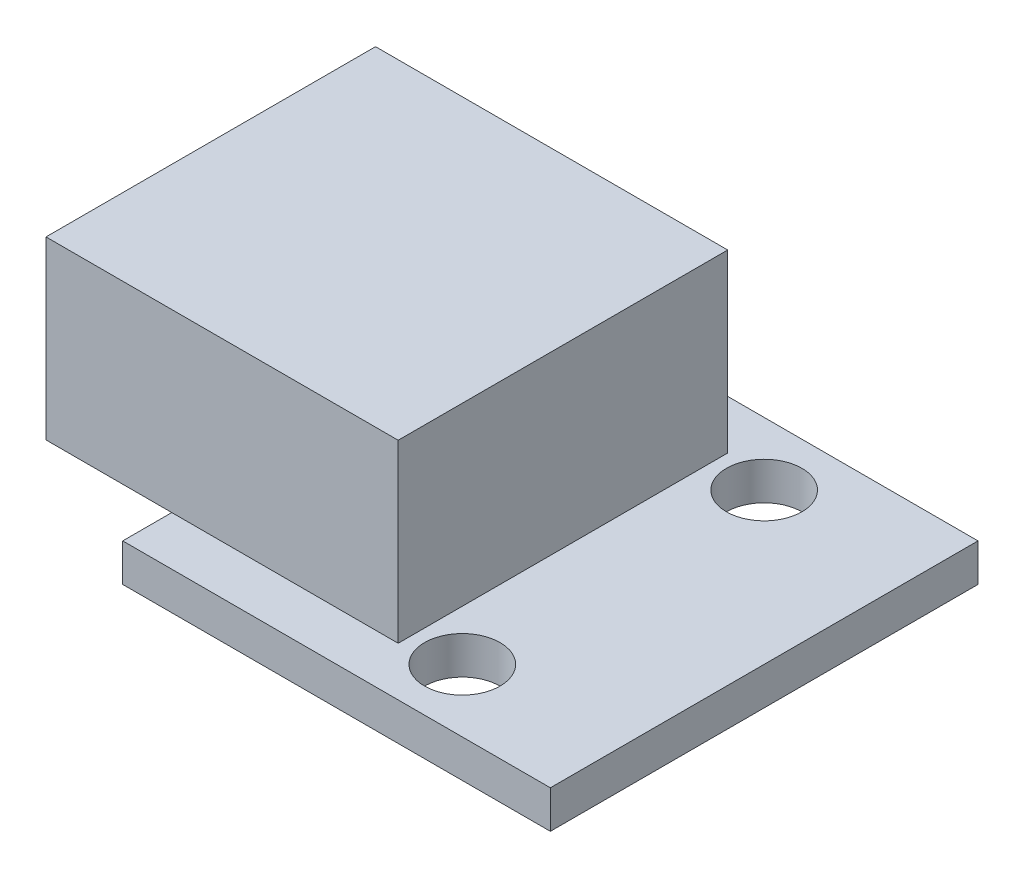
SolidWorks part; units mm, degrees
ref_plane "Front Plane" through (0, 0, 0) normal (0, 0, 1) x (1, 0, 0)
ref_plane "Top Plane" through (0, 0, 0) normal (0, 1, 0) x (1, 0, 0)
ref_plane "Right Plane" through (0, 0, 0) normal (1, 0, 0) x (0, 0, -1)
sketch "Sketch1" plane through (0, 0, 0) normal (0, 1, 0) x (1, 0, 0)
  line L0 (2.5, 6) -> (2.5, -6) construction
  line L1 (-8.5, -8.5) -> (8.5, -8.5)
  line L2 (-8.5, -8.5) -> (-8.5, 8.5)
  line L3 (-8.5, 8.5) -> (8.5, 8.5)
  line L4 (8.5, -8.5) -> (8.5, 8.5)
  line L5 (-8.5, -8.5) -> (8.5, 8.5) construction
  line L6 (-8.5, 8.5) -> (8.5, -8.5) construction
  circle A0 centre (2.5, 6) radius 1.5
  circle A1 centre (2.5, -6) radius 1.5
  point P0 (0, 0)
  point P10 (2.5, 0)
  dimension "D3" = 3
  dimension "D1" = 17
  dimension "D2" = 17
  dimension "D4" = 11
  dimension "D5" = 12
extrude "Boss-Extrude1" add sketch "Sketch1" along normal blind 1.5
sketch "Sketch2" plane through (0, 1.5, 0) normal (0, 1, 0) x (1, 0, 0)
  line L1 (-13.5, -6.55) -> (0.5, -6.55)
  line L2 (-13.5, -6.55) -> (-13.5, 6.55)
  line L3 (-13.5, 6.55) -> (0.5, 6.55)
  line L4 (0.5, -6.55) -> (0.5, 6.55)
  line L5 (-13.5, -6.55) -> (0.5, 6.55) construction
  line L6 (-13.5, 6.55) -> (0.5, -6.55) construction
  circle A0 centre (2.5, -6) radius 1.5 construction
  point P0 (-6.5, 0)
  point P8 (-0.5, 0)
  dimension "D4" = 3
  dimension "D1" = 13.1
  dimension "D2" = 14
  dimension "D3" = 1
extrude "Boss-Extrude2" add sketch "Sketch2" along normal blind 6.99
